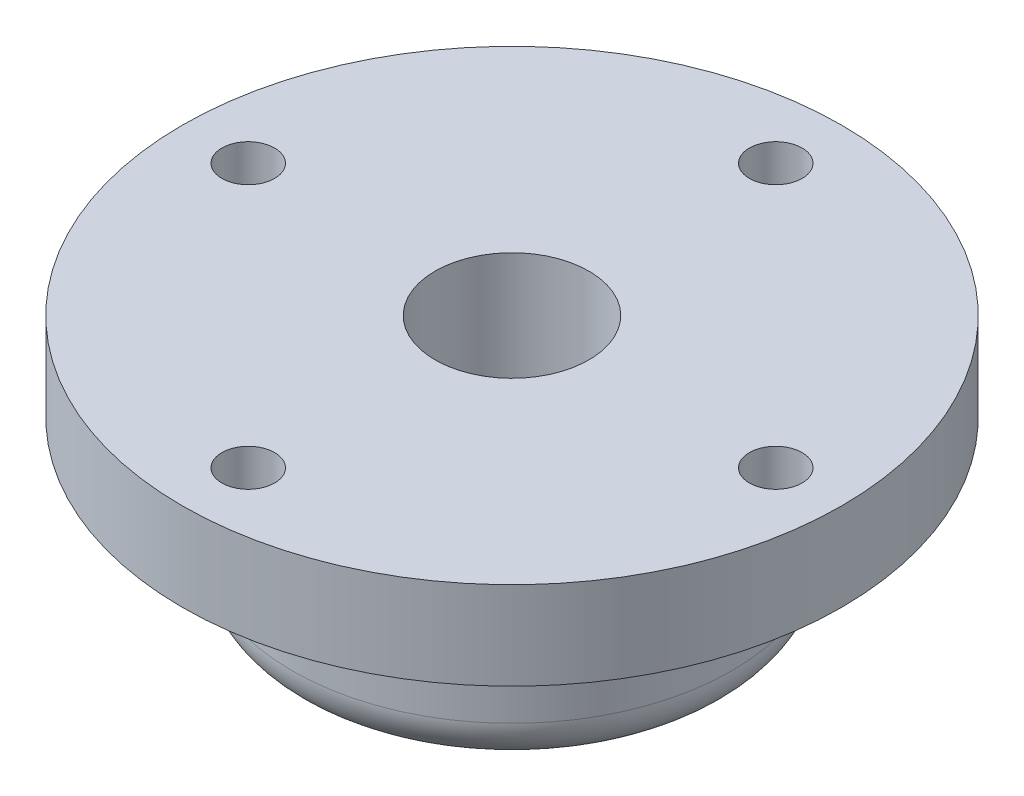
SolidWorks part; units mm, degrees
ref_plane "Alzado" through (0, 0, 0) normal (0, 0, 1) x (1, 0, 0)
ref_plane "Planta" through (0, 0, 0) normal (0, 1, 0) x (1, 0, 0)
ref_plane "Vista lateral" through (0, 0, 0) normal (1, 0, 0) x (0, 0, -1)
sketch "Croquis1" plane through (0, 0, 0) normal (0, 0, 1) x (1, 0, 0)
  line L0 (0, 71.8932) -> (0, -0.6073) construction
  line L2 (75, 42.3598) -> (50, 42.3598)
  line L3 (50, 42.3598) -> (50, 7.3598)
  line L4 (50, 7.3598) -> (17.5, 7.3598)
  line L5 (75, 42.3598) -> (75, 62.3598)
  line L6 (75, 62.3598) -> (17.5, 62.3598)
  line L7 (17.5, 42.3598) -> (17.5, 7.3598)
  line L8 (17.5, 62.3598) -> (17.5, 42.3598)
  dimension "D1" = 17.5
  dimension "D2" = 32.5
  dimension "D3" = 35
  dimension "D4" = 57.5
  dimension "D5" = 20
revolve "Revolución1" add sketch "Croquis1" angle 360 about L0
sketch "Croquis4" plane through (0, 42.3598, 0) normal (0, -1, 0) x (1, 0, 0)
  circle A0 centre (0, 0) radius 60 construction
  circle A1 centre (0, 60) radius 6
  circle A2 centre (60, 0) radius 6
  circle A3 centre (0, -60) radius 6
  circle A4 centre (-60, 0) radius 6
  point P14 (0, 0)
  dimension "D1" = 4
extrude "Cortar-Extruir1" cut sketch "Croquis4" against normal blind 29 and the other way through all
fillet "Redondeo3" radius 10 2 edges at (-17.5, 7.3598, 0) (-50, 7.3598, 0)
